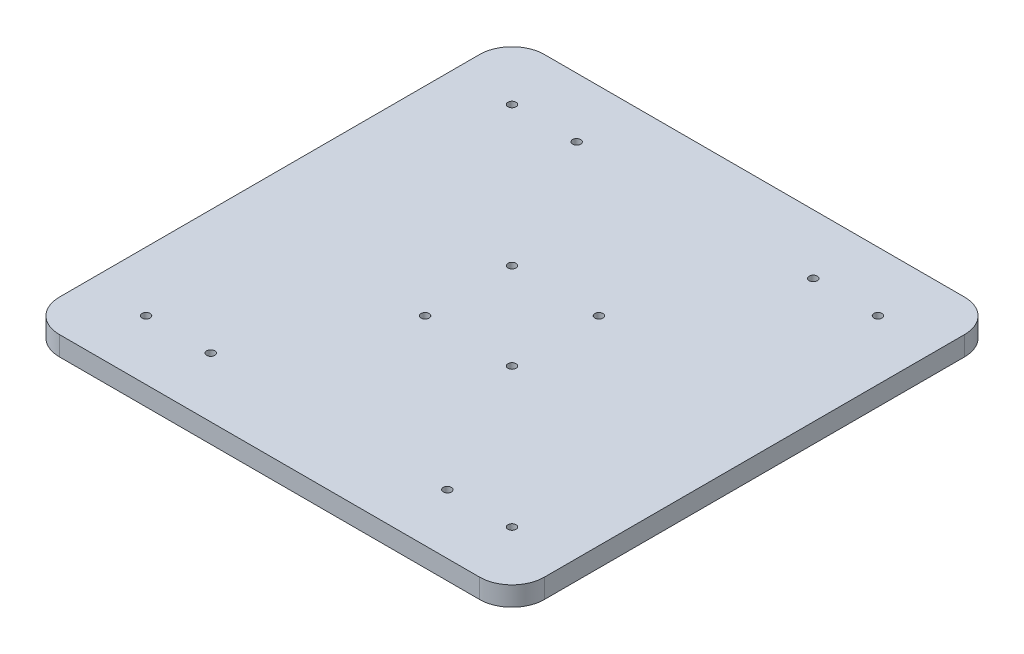
SolidWorks part; units mm, degrees
material "AISI 304"
ref_plane "前视基准面" through (0, 0, 0) normal (0, 0, 1) x (1, 0, 0)
ref_plane "上视基准面" through (0, 0, 0) normal (0, 1, 0) x (1, 0, 0)
ref_plane "右视基准面" through (0, 0, 0) normal (1, 0, 0) x (0, 0, -1)
other "Configuration Table"
sketch "草图1" plane through (0, 0, 0) normal (0, 1, 0) x (1, 0, 0)
  line L1 (-75, 75) -> (75, 75)
  line L2 (-75, 75) -> (-75, -75)
  line L3 (-75, -75) -> (75, -75)
  line L4 (75, 75) -> (75, -75)
  line L5 (-75, 75) -> (75, -75) construction
  line L6 (-75, -75) -> (75, 75) construction
  point P0 (0, 0)
  dimension "D1" = 150
  dimension "D2" = 150
extrude "凸台-拉伸1" add sketch "草图1" along normal blind 6
fillet "圆角1" radius 10 4 edges at (-75, 3, 75) (75, 3, 75) (75, 3, -75) (-75, 3, -75)
sketch "草图2" plane through (0, 6, 0) normal (0, 1, 0) x (1, 0, 0)
  line L0 (0, 0) -> (72.0711, 72.0711) construction
  arc A0 (75, 65) -> (65, 75) centre (65, 65) ccw construction
sketch "草图3" plane through (0, 0, 0) normal (0, -1, 0) x (1, 0, 0)
  line L0 (0, 0) -> (72.0711, 72.0711) construction
  arc A0 (75, 65) -> (65, 75) centre (65, 65) ccw construction
  circle A1 centre (56.5685, 56.5685) radius 1.25
  dimension "D1" = 2.5
  dimension "D2" = 80
extrude "切除-拉伸4" cut sketch "草图3" against normal through all
pattern_circular "阵列(圆周)2" count 4 over 360 about axis through (-0.0124, 0, -0.0124) along (0, 1, 0) of "切除-拉伸4"
sketch "草图7" plane through (0, 0, 0) normal (0, -1, 0) x (1, 0, 0)
  line L4 (65, 75) -> (-65, 75)
  line L5 (-75, 65) -> (-75, -65)
  line L6 (-65, -75) -> (65, -75)
  line L7 (75, -65) -> (75, 65)
  line L8 (65, 75) -> (-65, 75)
  line L9 (-75, 65) -> (-75, -65)
  line L10 (-65, -75) -> (65, -75)
  line L11 (75, -65) -> (75, 65)
  circle A0 centre (-56.5933, 56.5685) radius 1.25 construction
  circle A1 centre (-56.5933, -56.5933) radius 1.25 construction
  circle A2 centre (-56.5933, 56.5685) radius 1.25
  circle A3 centre (-56.5933, -56.5933) radius 1.25
  arc A4 (-65, 75) -> (-75, 65) centre (-65, 65) ccw
  arc A5 (-75, -65) -> (-65, -75) centre (-65, -65) ccw
  arc A6 (65, -75) -> (75, -65) centre (65, -65) ccw
  arc A7 (75, 65) -> (65, 75) centre (65, 65) ccw
  arc A8 (-65, 75) -> (-75, 65) centre (-65, 65) ccw
  arc A9 (-75, -65) -> (-65, -75) centre (-65, -65) ccw
  arc A10 (65, -75) -> (75, -65) centre (65, -65) ccw
  arc A11 (75, 65) -> (65, 75) centre (65, 65) ccw
  circle A12 centre (56.5685, 56.5685) radius 1.25 construction
  circle A13 centre (56.5685, -56.5933) radius 1.25 construction
  circle A14 centre (56.5685, 56.5685) radius 1.25
  circle A15 centre (56.5685, -56.5933) radius 1.25
  circle A16 centre (-36.5933, -56.5933) radius 1.25
  circle A17 centre (36.5685, -56.5933) radius 1.25
  circle A18 centre (-36.5933, 56.5685) radius 1.25
  circle A19 centre (36.5685, 56.5685) radius 1.25
  dimension "D1" = 0
  dimension "D2" = 2
  dimension "D3" = 2
  dimension "D4" = 2
  dimension "D5" = 2
extrude "切除-拉伸11" cut sketch "草图7" against normal blind 10 contours A18 | A19 | A16 | A17
sketch "草图9" plane through (0, 0, 0) normal (0, -1, 0) x (1, 0, 0)
  line L0 (-70.1773, 0) -> (106.2684, 0) construction
  line L1 (0, 72.4711) -> (0, -87.6775) construction
  line L2 (0, 0) -> (37.0368, 37.0368) construction
  circle A0 centre (13.435, 13.435) radius 1.25
  circle A1 centre (13.435, -13.435) radius 1.25
  circle A2 centre (-13.435, -13.435) radius 1.25
  circle A3 centre (-13.435, 13.435) radius 1.25
  point P18 (0, 0)
  dimension "D2" = 2.5
  dimension "D1" = 45
  dimension "D3" = 19
  dimension "D4" = 4
extrude "切除-拉伸12" cut sketch "草图9" against normal blind 10
